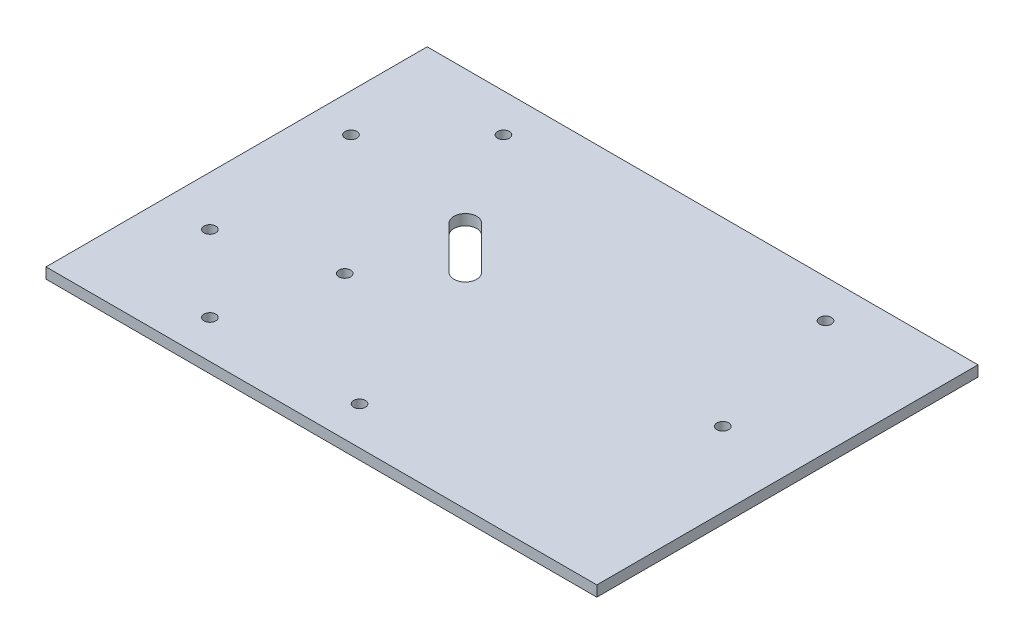
SolidWorks part; units mm, degrees
ref_plane "Front" through (0, 0, 0) normal (0, 0, 1) x (1, 0, 0)
ref_plane "Top" through (0, 0, 0) normal (0, 1, 0) x (1, 0, 0)
ref_plane "Right" through (0, 0, 0) normal (1, 0, 0) x (0, 0, -1)
sketch "Sketch1" plane through (0, 0, 0) normal (0, 1, 0) x (1, 0, 0)
  line L0 (-59.25, -20) -> (-39.25, -40) construction
  line L1 (-72.25, -50) -> (72.25, -50)
  line L2 (-72.25, -50) -> (-72.25, 50)
  line L3 (-72.25, 50) -> (72.25, 50)
  line L4 (72.25, -50) -> (72.25, 50)
  line L5 (-72.25, -50) -> (72.25, 50) construction
  line L6 (-72.25, 50) -> (72.25, -50) construction
  line L7 (-49.25, -30) -> (-31.5723, -12.3223) construction
  circle A0 centre (-59.25, -20) radius 1.55
  circle A1 centre (-39.25, -40) radius 1.55
  circle A2 centre (-31.5723, -12.3223) radius 1.55
  point P0 (0, 0)
  dimension "D3" = 3.1
  dimension "D4" = 3.1
  dimension "D7" = 33
  dimension "D8" = 13
  dimension "D10" = 3.1
  dimension "D1" = 100
  dimension "D2" = 144.5
  dimension "D5" = 30
  dimension "D6" = 10
  dimension "D9" = 25
extrude "Boss-Extrude1" add sketch "Sketch1" along normal blind 2.8
sketch "Sketch2" plane through (0, 2.8, 0) normal (0, 1, 0) x (1, 0, 0)
  line L0 (-27.25, 15) -> (-15.9363, 3.6863) construction
  line L1 (72.25, 50) -> (-72.25, 50) construction
  line L2 (-25.1287, 17.1213) -> (-13.815, 5.8076)
  line L3 (-29.3713, 12.8787) -> (-18.0576, 1.565)
  line L4 (-72.25, 50) -> (-72.25, -50) construction
  arc A1 (-25.1287, 17.1213) -> (-29.3713, 12.8787) centre (-27.25, 15) ccw
  arc A2 (-18.0576, 1.565) -> (-13.815, 5.8076) centre (-15.9363, 3.6863) ccw
  point P4 (-21.5931, 9.3431)
  dimension "D1" = 45
  dimension "D2" = 45
  dimension "D3" = 35
  dimension "D4" = 16
  dimension "D5" = 6
extrude "Cut-Extrude1" cut sketch "Sketch2" against normal up to next
sketch "Sketch3" plane through (0, 2.8, 0) normal (0, 1, 0) x (1, 0, 0)
  line L0 (-72.25, 50) -> (-72.25, -50) construction
  line L1 (72.25, 50) -> (-72.25, 50) construction
  line L2 (72.25, -50) -> (72.25, 50) construction
  line L3 (-72.25, -50) -> (72.25, -50) construction
  circle A0 centre (-62.25, 20) radius 1.55
  circle A1 centre (-42.25, 40) radius 1.55
  circle A2 centre (42.25, 40) radius 1.55
  circle A3 centre (0, -40) radius 1.55
  point P8 (0, 0)
  dimension "D1" = 3.1
  dimension "D2" = 3.1
  dimension "D3" = 3.1
  dimension "D4" = 3.1
  dimension "D5" = 30
  dimension "D6" = 10
  dimension "D7" = 30
  dimension "D8" = 10
  dimension "D9" = 30
  dimension "D10" = 72.25
  dimension "D11" = 10
extrude "Cut-Extrude2" cut sketch "Sketch3" against normal up to next
sketch "Sketch4" plane through (0, 2.8, 0) normal (0, 1, 0) x (1, 0, 0)
  line L0 (72.25, -50) -> (72.25, 50) construction
  line L1 (72.25, 50) -> (-72.25, 50) construction
  circle A0 centre (52.75, 2.56) radius 1.55
  dimension "D1" = 3.1
  dimension "D3" = 47.44
  dimension "D2" = 19.5
extrude "Cut-Extrude3" cut sketch "Sketch4" against normal up to next
